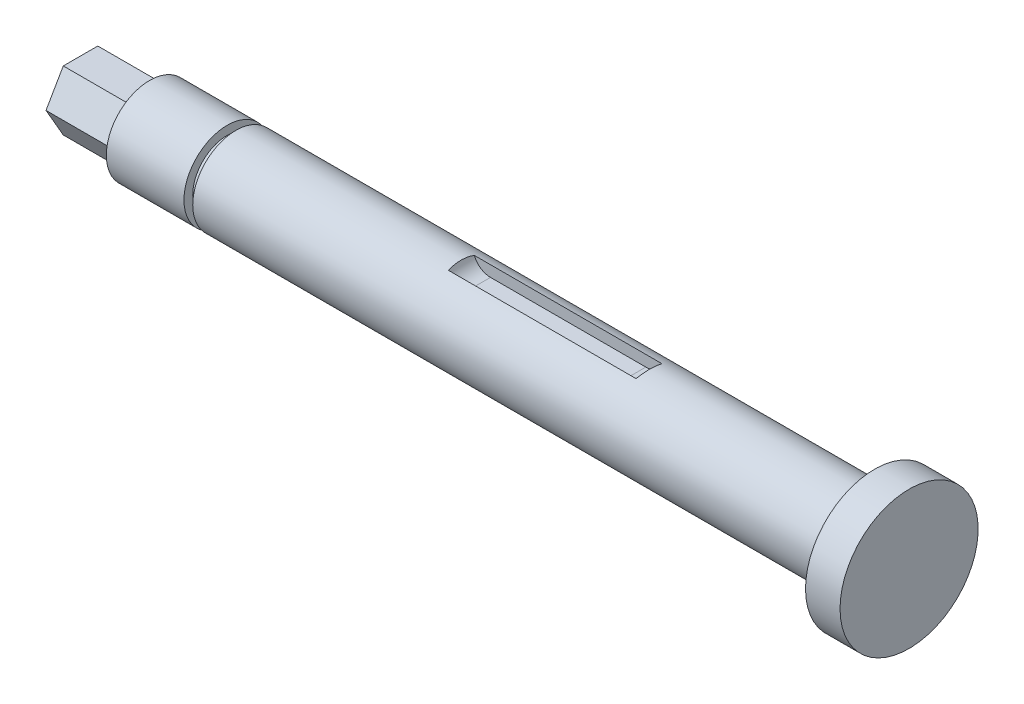
SolidWorks part; units mm, degrees
material "Chrome Stainless Steel"
ref_plane "Front Plane" through (0, 0, 0) normal (0, 0, 1) x (1, 0, 0)
ref_plane "Top Plane" through (0, 0, 0) normal (0, 1, 0) x (1, 0, 0)
ref_plane "Right Plane" through (0, 0, 0) normal (1, 0, 0) x (0, 0, -1)
sketch "Base Sketch" plane through (0, 0, 0) normal (0, 0, 1) x (1, 0, 0)
  line L0 (-28.2307, 0) -> (67.9373, 0) construction
  line L1 (0, 0) -> (152.4, 0)
  line L2 (152.4, 0) -> (152.4, 12.7)
  line L3 (152.4, 12.7) -> (146.05, 12.7)
  line L4 (146.05, 12.7) -> (146.05, 7.9375)
  line L5 (146.05, 7.9375) -> (28.575, 7.9375)
  line L6 (28.575, 7.9375) -> (28.575, 6.3373)
  line L7 (28.575, 6.3373) -> (26.9748, 6.3373)
  line L8 (26.9748, 6.3373) -> (26.9748, 7.9502)
  line L9 (26.9748, 7.9502) -> (12.7, 7.9502)
  line L10 (12.7, 7.9502) -> (12.7, 6.35)
  line L11 (12.7, 6.35) -> (0, 6.35)
  line L12 (0, 6.35) -> (0, 0)
  point P13 (0, 0)
  dimension "D1" = 1.6002
  dimension "D2" = 12.7
  dimension "D3" = 133.35
  dimension "D4" = 12.7
  dimension "D5" = 1.6002
  dimension "D6" = 117.475
  dimension "D7" = 6.35
  dimension "D8" = 7.9375
  dimension "D9" = 7.9502
  dimension "D10" = 6.35
revolve "Base" add sketch "Base Sketch" angle 360 about L0
sketch "Keyway Sketch" plane through (0, 0, 0) normal (0, 0, 1) x (1, 0, 0)
  line L0 (0, 47.0361) -> (0, -56.2311) construction
  line L1 (0, 14.2875) -> (178.0526, 14.2875) construction
  line L2 (146.05, 7.9375) -> (28.575, 7.9375) construction
  line L3 (69.85, 14.2875) -> (104.775, 14.2875)
  line L4 (0, 5.5499) -> (164.0485, 5.5499) construction
  line L5 (69.85, 14.2875) -> (69.85, 8.7249)
  line L6 (104.775, 14.2875) -> (104.775, 8.7249)
  line L7 (101.6, 5.5499) -> (73.025, 5.5499)
  arc A0 (69.85, 8.7249) -> (73.025, 5.5499) centre (73.025, 8.7249) ccw
  arc A1 (104.775, 8.7249) -> (101.6, 5.5499) centre (101.6, 8.7249) cw
  point P17 (0, 0)
  dimension "D5" = 3.175
  dimension "D6" = 3.175
  dimension "D1" = 6.35
  dimension "D2" = 69.85
  dimension "D3" = 34.925
  dimension "D4" = 2.3876
extrude "Keyway" cut sketch "Keyway Sketch" against normal mid plane 4.7625
sketch "Hexagonal Sketch" plane through (0, 0, 0) normal (-1, 0, 0) x (0, 0, 1)
  line L1 (3.175, 5.4993) -> (-3.175, 5.4993)
  line L2 (-3.175, 5.4993) -> (-6.35, 0)
  line L3 (-6.35, 0) -> (-3.175, -5.4993)
  line L4 (-3.175, -5.4993) -> (3.175, -5.4993)
  line L5 (3.175, -5.4993) -> (6.35, 0)
  line L6 (6.35, 0) -> (3.175, 5.4993)
  circle A0 centre (0, 0) radius 6.35 construction
  dimension "D1" = 12.7
extrude "Hexagonal Cut" cut sketch "Hexagonal Sketch" against normal up to surface (12.7 mm away) flip side to cut up to face at (12.7, 0, 6.35)
